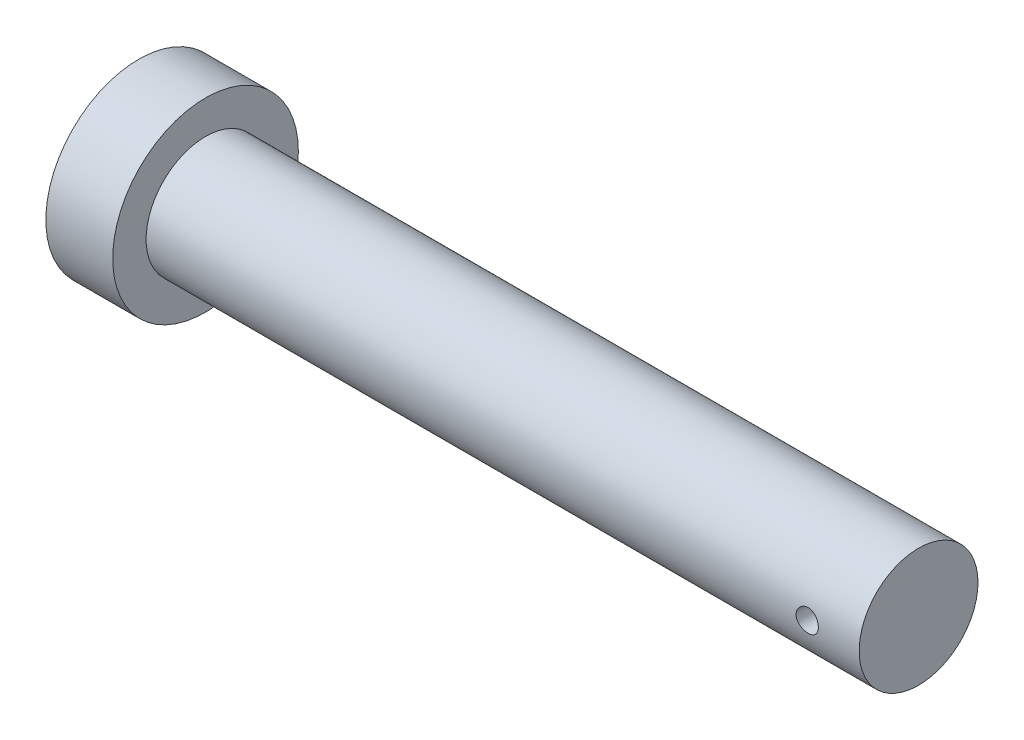
SolidWorks part; units mm, degrees
material "AISI 4130 Steel, normalized at 870C"
ref_plane "Front Plane" through (0, 0, 0) normal (0, 0, 1) x (1, 0, 0)
ref_plane "Top Plane" through (0, 0, 0) normal (0, 1, 0) x (1, 0, 0)
ref_plane "Right Plane" through (0, 0, 0) normal (1, 0, 0) x (0, 0, -1)
sketch "Sketch1" plane through (0, 0, 0) normal (1, 0, 0) x (0, 0, -1)
  circle A0 centre (0, 0) radius 12.5
extrude "Boss-Extrude1" add sketch "Sketch1" along normal blind 9
sketch "Sketch2" plane through (9, 0, 0) normal (1, 0, 0) x (0, 0, -1)
  circle A0 centre (0, 0) radius 8
extrude "Boss-Extrude2" add sketch "Sketch2" along normal blind 96
sketch "Sketch3" plane through (105, 0, 0) normal (1, 0, 0) x (0, 0, -1)
  line L0 (-8, 0) -> (8, 0) construction
  circle A0 centre (0, 0) radius 8 construction
ref_plane "Plane1" through (0, 0, 8) normal (0, 0, 1) x (1, 0, 0)
sketch "Sketch4" plane through (0, 0, 8) normal (0, 0, 1) x (1, 0, 0)
  line L0 (9, -8) -> (9, 8) construction
  circle A0 centre (98, 0) radius 1.5
  dimension "D1" = 89
extrude "Cut-Extrude1" cut sketch "Sketch4" against normal blind 96
scale "Escala1" scale about centroid uniform scaling yes scale factor 0.5
